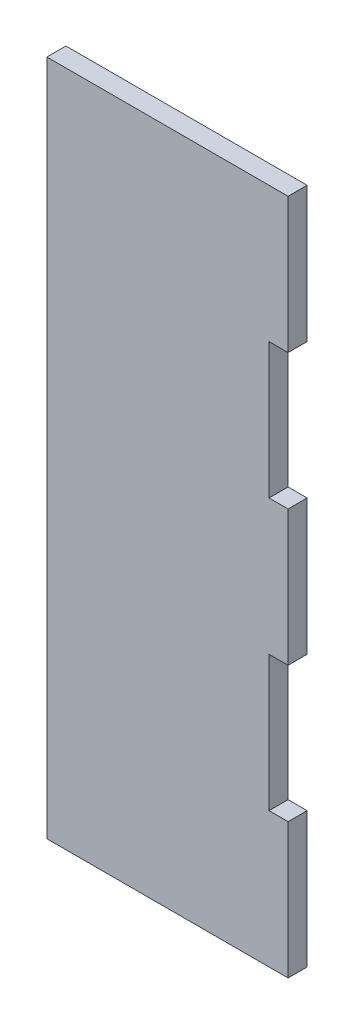
SolidWorks part; units mm, degrees
ref_plane "Front Plane" through (0, 0, 0) normal (0, 0, 1) x (1, 0, 0)
ref_plane "Top Plane" through (0, 0, 0) normal (0, 1, 0) x (1, 0, 0)
ref_plane "Right Plane" through (0, 0, 0) normal (1, 0, 0) x (0, 0, -1)
sketch "Sketch2" plane through (0, 0, 0) normal (0, 0, 1) x (1, 0, 0)
  line L41 (114, 192) -> (105, 192)
  line L42 (114, 0) -> (114, 64)
  line L43 (114, 128) -> (114, 192)
  line L44 (114, 256) -> (114, 320)
  line L45 (105, 256) -> (105, 192)
  line L46 (114, 64) -> (105, 64)
  line L47 (114, 128) -> (105, 128)
  line L48 (114, 320) -> (0, 320)
  line L49 (0, 0) -> (114, 0)
  line L50 (114, 256) -> (105, 256)
  line L51 (105, 128) -> (105, 64)
  line L52 (0, 320) -> (0, 0)
  dimension "D3" = 9
  dimension "D10" = 64
  dimension "D11" = 64
  dimension "D12" = 64
  dimension "D13" = 9
  dimension "D14" = 105
  dimension "D15" = 320
  dimension "D16" = 64
extrude "Boss-Extrude1" add sketch "Sketch2" along normal blind 9
